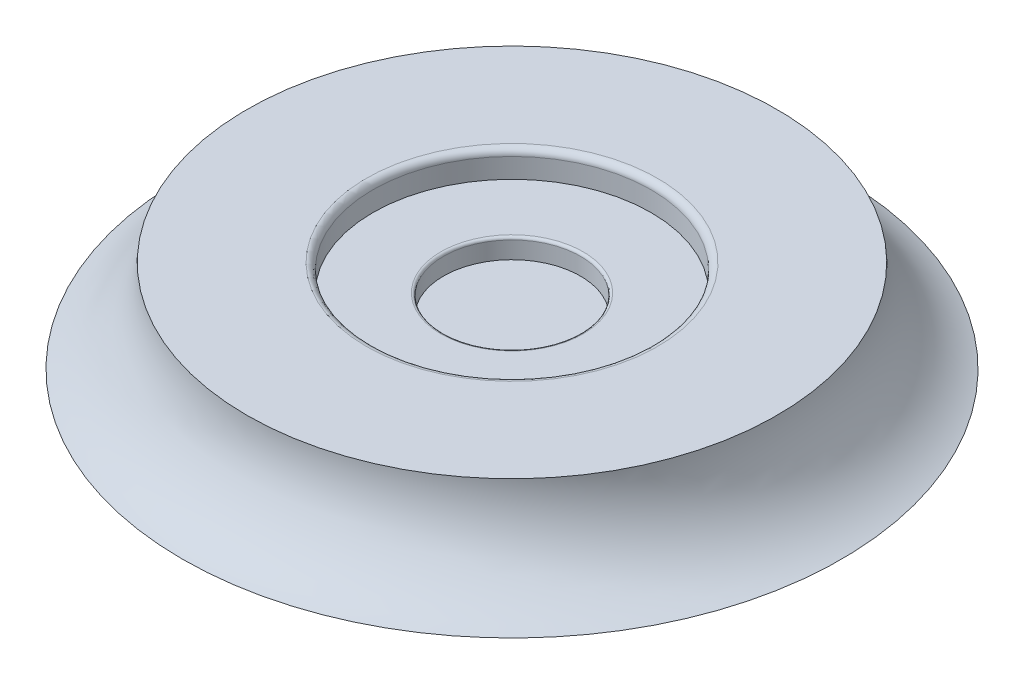
SolidWorks part; units mm, degrees
ref_plane "Front Plane" through (0, 0, 0) normal (0, 0, 1) x (1, 0, 0)
ref_plane "Top Plane" through (0, 0, 0) normal (0, 1, 0) x (1, 0, 0)
ref_plane "Right Plane" through (0, 0, 0) normal (1, 0, 0) x (0, 0, -1)
sketch "Sketch1" plane through (0, 0, 0) normal (1, 0, 0) x (0, 0, -1)
  line L2 (0, 0) -> (-25, 0)
  line L3 (-10.55, 7) -> (-10.55, 5)
  line L4 (-10.55, 5) -> (0, 5)
  line L5 (0, 5) -> (0, 0)
  line L6 (-10.55, 7) -> (-20.1025, 7)
  arc A1 (-20.1025, 7) -> (-25, 0) centre (-27.5539, 7) cw
  dimension "D3" = 10.55
  dimension "D1" = 2
  dimension "D2" = 5
  dimension "D4" = 25
revolve "Revolve1" add sketch "Sketch1" angle 360 about L5
fillet "Fillet1" radius 0.5 1 edges at (0, 7, 10.55)
sketch "Sketch2" plane through (0, 5, 0) normal (0, 1, 0) x (1, 0, 0)
  circle A0 centre (0, 0) radius 5.2
  dimension "D1" = 10.4
extrude "Cut-Extrude1" cut sketch "Sketch2" against normal blind 1.5
fillet "Fillet2" radius 0.2 1 edges at (0, 5, 5.2)
